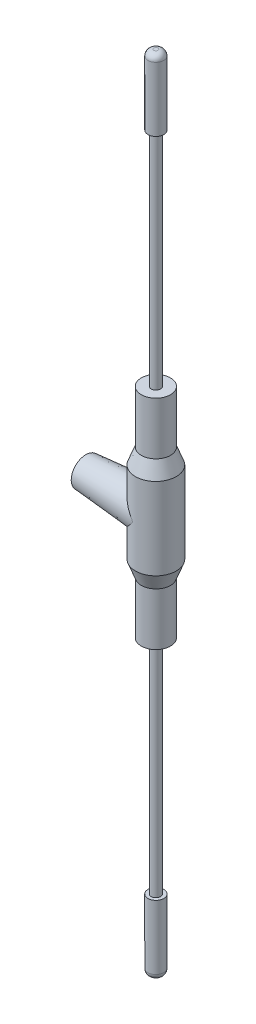
SolidWorks part; units mm, degrees
ref_plane "Alzado" through (0, 0, 0) normal (0, 0, 1) x (1, 0, 0)
ref_plane "Planta" through (0, 0, 0) normal (0, 1, 0) x (1, 0, 0)
ref_plane "Vista lateral" through (0, 0, 0) normal (1, 0, 0) x (0, 0, -1)
sketch "Croquis1" plane through (0, 0, 0) normal (0, 0, 1) x (1, 0, 0)
  line L0 (0, 7) -> (0, -7)
  line L1 (0, -7) -> (0, -10)
  line L2 (0, 0) -> (-3.5, 0) construction
  line L3 (-3.5, 7) -> (-3.5, -7)
  line L4 (-3.5, -7) -> (-2.5, -9.6451)
  line L5 (-2.5, -9.6451) -> (-2.5, -18.6451)
  line L6 (-2.5, -18.6451) -> (-0.8, -18.6451)
  line L7 (-0.8, -18.6451) -> (-0.8, -56.6451)
  line L8 (-0.8, -56.6451) -> (-1.35, -56.6451)
  line L9 (-1.35, -56.6451) -> (-1.35, -68.6451)
  line L10 (-1.35, -68.6451) -> (0, -68.6451)
  line L11 (0, -68.6451) -> (0, -10)
  line L12 (0, 7) -> (0, 10)
  line L13 (0, 68.6451) -> (0, 10)
  line L14 (-1.35, 68.6451) -> (0, 68.6451)
  line L15 (-1.35, 56.6451) -> (-1.35, 68.6451)
  line L16 (-0.8, 56.6451) -> (-1.35, 56.6451)
  line L17 (-0.8, 18.6451) -> (-0.8, 56.6451)
  line L18 (-2.5, 18.6451) -> (-0.8, 18.6451)
  line L19 (-2.5, 9.6451) -> (-2.5, 18.6451)
  line L20 (-3.5, 7) -> (-2.5, 9.6451)
  dimension "D1" = 7
  dimension "D2" = 3
  dimension "D3" = 7
  dimension "D4" = 9
  dimension "D5" = 2.5
  dimension "D6" = 3.5
  dimension "D7" = 1.7
  dimension "D8" = 0.55
  dimension "D9" = 38
  dimension "D10" = 12
revolve "Revolución1" add sketch "Croquis1" angle 360 about L13
sketch "Croquis2" plane through (0, 0, 0) normal (0, 0, 1) x (1, 0, 0)
  line L0 (0, 0) -> (0, 3.5)
  line L1 (0, 0) -> (-12, 0)
  line L2 (-12, 0) -> (-12, 2.5)
  line L3 (-12, 2.5) -> (0, 3.5)
revolve "Revolución2" add sketch "Croquis2" angle 360 about L1
fillet "Redondeo1" radius 1 2 edges at (-1.35, 68.6451, 0) (-1.35, -68.6451, 0)
